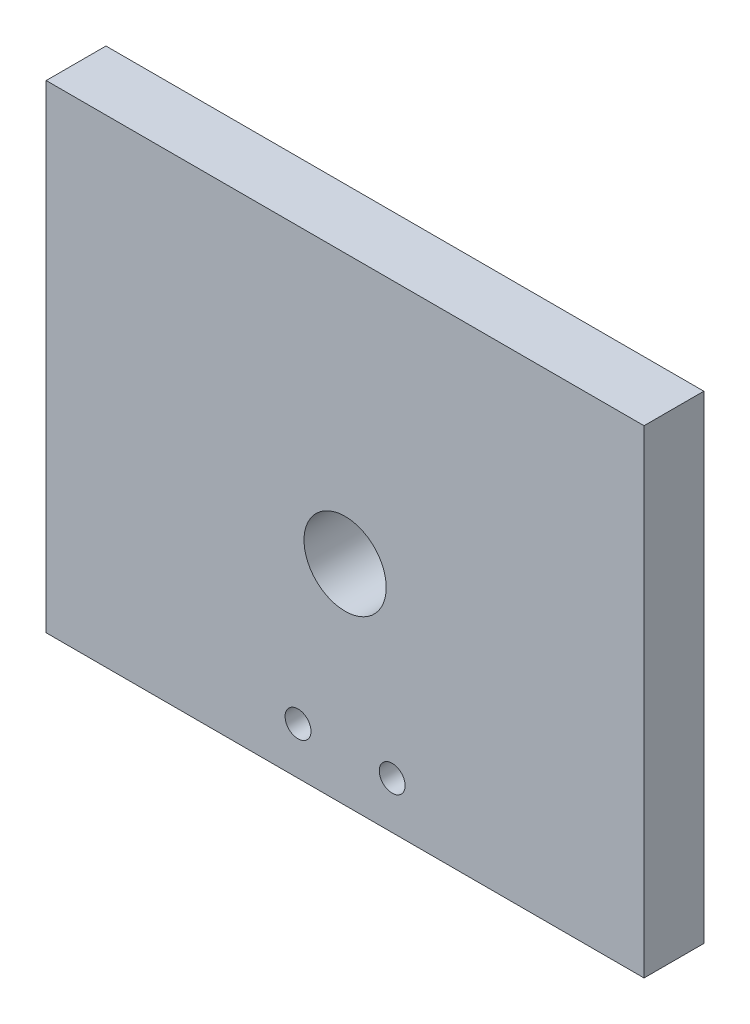
SolidWorks part; units mm, degrees
material "6061 Alloy"
ref_plane "Front Plane" through (0, 0, 0) normal (0, 0, 1) x (1, 0, 0)
ref_plane "Top Plane" through (0, 0, 0) normal (0, 1, 0) x (1, 0, 0)
ref_plane "Right Plane" through (0, 0, 0) normal (1, 0, 0) x (0, 0, -1)
sketch "Sketch1" plane through (0, 0, 0) normal (0, 0, 1) x (1, 0, 0)
  line L1 (-63.5, 50.8) -> (63.5, 50.8)
  line L2 (-63.5, 50.8) -> (-63.5, -50.8)
  line L3 (-63.5, -50.8) -> (63.5, -50.8)
  line L4 (63.5, 50.8) -> (63.5, -50.8)
  line L5 (-63.5, 50.8) -> (63.5, -50.8) construction
  line L6 (-63.5, -50.8) -> (63.5, 50.8) construction
  point P0 (0, 0)
  dimension "D1" = 127
  dimension "D2" = 101.6
extrude "Boss-Extrude1" add sketch "Sketch1" along normal mid plane 12.7
hole_wizard "Hole1" [suppressed] positions "Sketch4" profile "Sketch3" legacy
sketch "Sketch4" plane through (0, 0, -6.35) normal (0, 0, -1) x (-1, 0, 0)
  line L1 (0, -6.35) -> (0, 0) construction
  line L3 (63.5, -50.8) -> (-63.5, -50.8) construction
  point P0 (0, -6.35)
  dimension "D1" = 44.45
sketch "Sketch3" plane through (0, -6.35, -6.35) normal (1, 0, 0) x (0, 1, 0)
  line L0 (0, 0) -> (0, 12.7)
  line L1 (0, 12.7) -> (6.35, 12.7)
  line L2 (6.35, 12.7) -> (6.35, 9.525)
  line L3 (6.35, 9.525) -> (8.7313, 9.525)
  line L4 (8.7313, 9.525) -> (8.7313, 0)
  line L5 (8.7313, 0) -> (0, 0)
  line L6 (0, 110) -> (0, -10) construction
  dimension "Diameter" = 12.7
  dimension "Depth" = 12.7
  dimension "C-Bore Diameter" = 17.4625
  dimension "C-Bore Depth" = 9.525
hole_wizard "Hole2" positions "Sketch6" profile "Sketch7" legacy end condition up to next
sketch "Sketch6" plane through (0, 0, 6.35) normal (0, 0, 1) x (1, 0, 0)
  line L0 (0, -6.35) -> (0, 0) construction
  line L2 (-63.5, -50.8) -> (63.5, -50.8) construction
  point P0 (0, -6.35)
  dimension "D1" = 44.45
sketch "Sketch7" plane through (0, -6.35, 6.35) normal (1, 0, 0) x (0, -1, 0)
  line L0 (0, 0) -> (0, 12.7)
  line L1 (0, 12.7) -> (8.7313, 12.7)
  line L2 (8.7313, 12.7) -> (8.7313, 0)
  line L3 (8.7313, 0) -> (0, 0)
  line L4 (0, 110) -> (0, -10) construction
  dimension "Diameter" = 17.4625
  dimension "Depth" = 12.7
hole_wizard "Hole3" [suppressed] positions "Sketch9" profile "Sketch8" legacy
sketch "Sketch9" plane through (0, 0, -6.35) normal (0, 0, -1) x (-1, 0, 0)
  line L4 (0, 0) -> (0, -19.05) construction
  line L6 (-38.1, -19.05) -> (38.1, -19.05) construction
  line L8 (63.5, -50.8) -> (-63.5, -50.8) construction
  point P8 (-38.1, -19.05)
  point P9 (38.1, -19.05)
  dimension "D1" = 76.2
  dimension "D2" = 31.75
sketch "Sketch8" plane through (38.1, -19.05, -6.35) normal (1, 0, 0) x (0, 1, 0)
  line L0 (0, 0) -> (0, 12.7)
  line L1 (0, 12.7) -> (6.35, 12.7)
  line L2 (6.35, 12.7) -> (6.35, 0)
  line L3 (6.35, 0) -> (0, 0)
  line L4 (0, 110) -> (0, -10) construction
  dimension "Diameter" = 12.7
  dimension "Depth" = 12.7
hole_wizard "Tapped Hole for #10-32 Helicoil1" [suppressed] positions "Sketch11" profile "Sketch12" tap size "#10-32" standard "Helicoil® Inch"
sketch "Sketch11" plane through (63.5, 0, 0) normal (1, 0, 0) x (0, 0, -1)
  line L0 (0, -19.05) -> (0, -50.8) construction
  line L1 (-6.35, -50.8) -> (6.35, -50.8) construction
  point P0 (0, -19.05)
  dimension "D1" = 31.75
sketch "Sketch12" plane through (63.5, -19.05, 0) normal (0, 1, 0) x (0, 0, -1)
  line L0 (0, 0) -> (0, 127)
  line L1 (0, 127) -> (2.5527, 127)
  line L2 (2.5527, 127) -> (2.5527, 0)
  line L5 (2.5527, 0) -> (0, 0)
  line L11 (0, -6.35) -> (0, 107.95) construction
  dimension "Thru Tap Drill Dia." = 5.1054
  dimension "Thru Tap Drill Depth" = 127
cosmetic thread "Hole Thread1" [suppressed] parameters "D1"=11.43, "D2"=5.936
mirror "Mirror1" [suppressed] about plane through (0, 0, 0) normal (1, 0, 0)
hole_wizard "Tapped Hole for #10-32 Helicoil2" [suppressed] positions "Sketch14" profile "Sketch13" tap size "#10-32" standard "Helicoil® Inch"
sketch "Sketch14" plane through (0, -50.8, 0) normal (0, -1, 0) x (-1, 0, 0)
  line L0 (63.5, 0) -> (-63.5, 0) construction
  line L1 (63.5, -6.35) -> (63.5, 6.35) construction
  line L2 (-63.5, -6.35) -> (-63.5, 6.35) construction
  point P8 (44.45, 0)
  point P10 (-44.45, 0)
  dimension "D1" = 19.05
  dimension "D2" = 19.05
sketch "Sketch13" plane through (-44.45, -50.8, 0) normal (1, 0, 0) x (0, 0, -1)
  line L0 (0, 0) -> (0, 39.6338)
  line L1 (0, 39.6338) -> (2.5527, 38.1)
  line L2 (2.5527, 38.1) -> (2.5527, 0)
  line L5 (2.5527, 0) -> (0, 0)
  line L10 (0, 39.6338) -> (-2.5527, 38.1) construction
  line L11 (0, -6.35) -> (0, 107.95) construction
  dimension "Tap Drill Dia." = 5.1054
  dimension "Tap Drill Depth" = 38.1
  dimension "Drill Angle" = 118
cosmetic thread "Hole Thread2" [suppressed] parameters "D1"=11.43, "D2"=5.936
cosmetic thread "Hole Thread3" [suppressed] parameters "D1"=11.43, "D2"=5.936
hole_wizard " M4 Clearance Hole1" positions "Sketch16" profile "Sketch15" hole size "M5" standard "ANSI Metric" end condition through all
sketch "Sketch16" plane through (0, 0, 6.35) normal (0, 0, 1) x (1, 0, 0)
  line L0 (-10, -40.8) -> (10, -40.8) construction
  line L1 (0, -40.8) -> (0, 0) construction
  line L3 (-63.5, -50.8) -> (63.5, -50.8) construction
  point P1 (-10, -40.8)
  point P2 (10, -40.8)
  dimension "D1" = 20
  dimension "D2" = 10
sketch "Sketch15" plane through (-10, -40.8, 6.35) normal (1, 0, 0) x (0, -1, 0)
  line L0 (0, 0) -> (0, 12.7)
  line L1 (0, 12.7) -> (2.75, 12.7)
  line L2 (2.75, 12.7) -> (2.75, 0)
  line L5 (2.75, 0) -> (0, 0)
  line L11 (0, -6.35) -> (0, 107.95) construction
  dimension "Thru Hole Dia." = 5.5
  dimension "Thru Hole Depth" = 12.7
